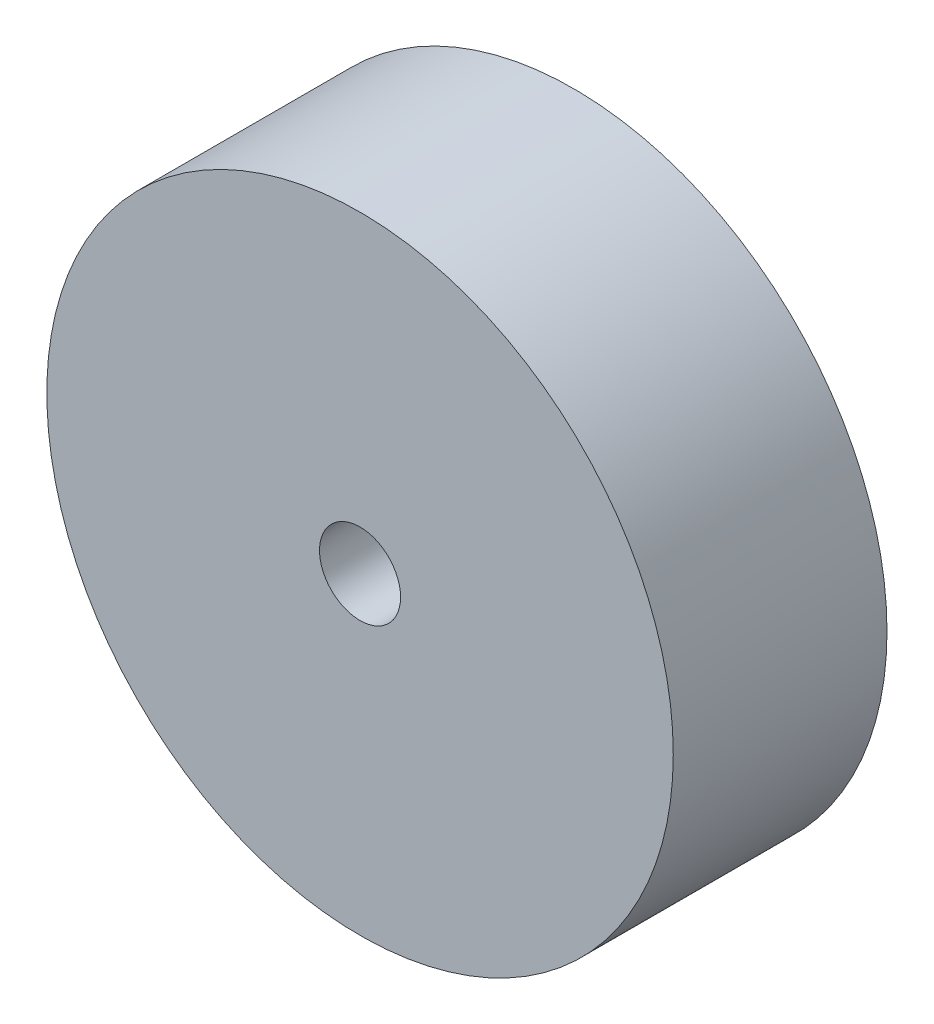
SolidWorks part; units mm, degrees
ref_plane "Front Plane" through (0, 0, 0) normal (0, 0, 1) x (1, 0, 0)
ref_plane "Top Plane" through (0, 0, 0) normal (0, 1, 0) x (1, 0, 0)
ref_plane "Right Plane" through (0, 0, 0) normal (1, 0, 0) x (0, 0, -1)
sketch "Sketch1" plane through (0, 0, 0) normal (0, 0, 1) x (1, 0, 0)
  circle A0 centre (-29.0823, -1.7038) radius 8.5
  dimension "D1" = 17
extrude "Boss-Extrude1" add sketch "Sketch1" along normal blind 5.8
sketch "Sketch2" plane through (0, 0, 0) normal (0, 0, -1) x (-1, 0, 0)
  circle A0 centre (29.0823, -1.7038) radius 8
  dimension "D1" = 16
extrude "Cut-Extrude1" cut sketch "Sketch2" against normal blind 3.2
sketch "Sketch3" plane through (0, 0, 3.2) normal (0, 0, -1) x (-1, 0, 0)
  circle A0 centre (29.0823, -1.7038) radius 1
  dimension "D1" = 2
extrude "Boss-Extrude2" add sketch "Sketch3" along normal blind 3.2
chamfer "Chamfer1" distance 2.65 angle 49 1 edges at (-30.0823, -1.7038, 3.2)
sketch "Sketch4" plane through (0, 0, 0) normal (0, 0, -1) x (-1, 0, 0)
  circle A0 centre (29.0823, -1.7038) radius 2.1
  dimension "D1" = 4.2
extrude "Boss-Extrude3" add sketch "Sketch4" against normal blind 3
sketch "Sketch5" plane through (0, 0, 0) normal (0, 0, -1) x (-1, 0, 0)
  circle A0 centre (29.0823, -1.7038) radius 0.85
  dimension "D1" = 1.7
extrude "Cut-Extrude2" cut sketch "Sketch5" against normal through all
sketch "Sketch6" plane through (0, 0, 5.8) normal (0, 0, 1) x (1, 0, 0)
  circle A0 centre (-29.0823, -1.7038) radius 1.1
  dimension "D1" = 2.2
extrude "Cut-Extrude3" cut sketch "Sketch6" against normal blind 3
